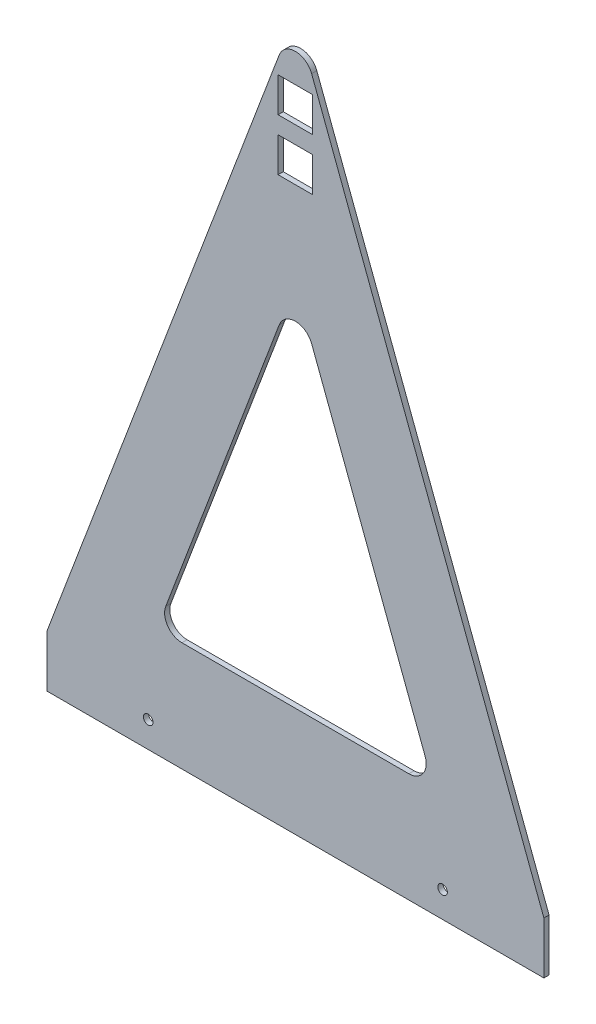
SolidWorks part; units mm, degrees
ref_plane "Alzado" through (0, 0, 0) normal (0, 0, 1) x (1, 0, 0)
ref_plane "Planta" through (0, 0, 0) normal (0, 1, 0) x (1, 0, 0)
ref_plane "Vista lateral" through (0, 0, 0) normal (1, 0, 0) x (0, 0, -1)
sketch "Croquis1" plane through (0, 0, 0) normal (0, 0, 1) x (1, 0, 0)
  line L0 (0, -2892.9169) -> (0, 141752.9275) construction
  line L1 (-143.5, 0) -> (143.5, 0)
  line L2 (143.5, 0) -> (143.5, 30)
  line L3 (143.5, 30) -> (9.3552, 385.2267)
  line L4 (-143.5, 30) -> (-9.3552, 385.2267)
  line L5 (-143.5, 0) -> (-143.5, 30)
  line L7 (-10, 375) -> (10, 375)
  line L8 (-10, 375) -> (-10, 355)
  line L9 (-10, 355) -> (10, 355)
  line L10 (10, 375) -> (10, 355)
  line L11 (-10, 375) -> (10, 355) construction
  line L12 (-10, 355) -> (10, 375) construction
  line L13 (-10, 345) -> (10, 345)
  line L14 (-10, 345) -> (-10, 325)
  line L15 (-10, 325) -> (10, 325)
  line L16 (10, 345) -> (10, 325)
  line L17 (-10, 345) -> (10, 325) construction
  line L18 (-10, 325) -> (10, 345) construction
  arc A0 (9.3552, 385.2267) -> (-9.3552, 385.2267) centre (0, 381.6939) ccw
  point P1 (0, 365)
  point P9 (0, 0)
  point P14 (0, 335)
  point P21 (0, 410)
  dimension "D10" = 10
  dimension "D1" = 143.5
  dimension "D2" = 30
  dimension "D3" = 410
  dimension "D4" = 20
  dimension "D5" = 20
  dimension "D6" = 375
  dimension "D7" = 20
  dimension "D8" = 20
  dimension "D9" = 345
extrude "Saliente-Extruir1" add sketch "Croquis1" along normal blind 3
hole_wizard "Taladro de margen para M52" positions "Croquis2" profile "Croquis3" hole size "M5" standard "ISO" end condition through all
sketch "Croquis2" plane through (0, 0, 0) normal (0, 0, -1) x (-1, 0, 0)
  point P0 (-85, 15)
  point P2 (85, 15)
  dimension "D1" = 170
  dimension "D2" = 85
  dimension "D3" = 15
sketch "Croquis3" plane through (85, 15, 0) normal (1, 0, 0) x (0, 1, 0)
  line L0 (0, 0) -> (0, 3)
  line L1 (0, 3) -> (2.75, 3)
  line L2 (2.75, 3) -> (2.75, 0)
  line L5 (2.75, 0) -> (0, 0)
  line L11 (0, -6.35) -> (0, 107.95) construction
  dimension "Diámetro de taladro hasta el siguiente" = 5.5
  dimension "Profundidad de taladro hasta el siguiente" = 3
sketch "Croquis4" plane through (0, 0, 0) normal (0, 0, -1) x (-1, 0, 0)
  line L0 (0, -1000) -> (0, 49000) construction
  line L1 (9.3552, 250.2267) -> (74.8896, 76.6861)
  line L2 (65.5344, 63.1533) -> (-65.5344, 63.1533)
  line L3 (9.3552, 385.2267) -> (143.5, 30) construction
  line L4 (143.5, 0) -> (-143.5, 0) construction
  line L5 (-9.3552, 250.2267) -> (-74.8896, 76.6861)
  arc A0 (74.8896, 76.6861) -> (65.5344, 63.1533) centre (65.5344, 73.1533) cw
  arc A1 (-74.8896, 76.6861) -> (-65.5344, 63.1533) centre (-65.5344, 73.1533) ccw
  arc A2 (9.3552, 250.2267) -> (-9.3552, 250.2267) centre (0, 246.6939) ccw
  point P11 (0, 63.1533)
  point P13 (80, 63.1533)
  point P16 (-80, 63.1533)
  point P19 (0, 275)
  dimension "D3" = 10
  dimension "D1" = 80
  dimension "D2" = 275
extrude "Cortar-Extruir1" cut sketch "Croquis4" against normal blind 3
ref_plane "Plano1" through (143.5, 0, 3) normal (1, 0, 0) x (0, 0, -1)
